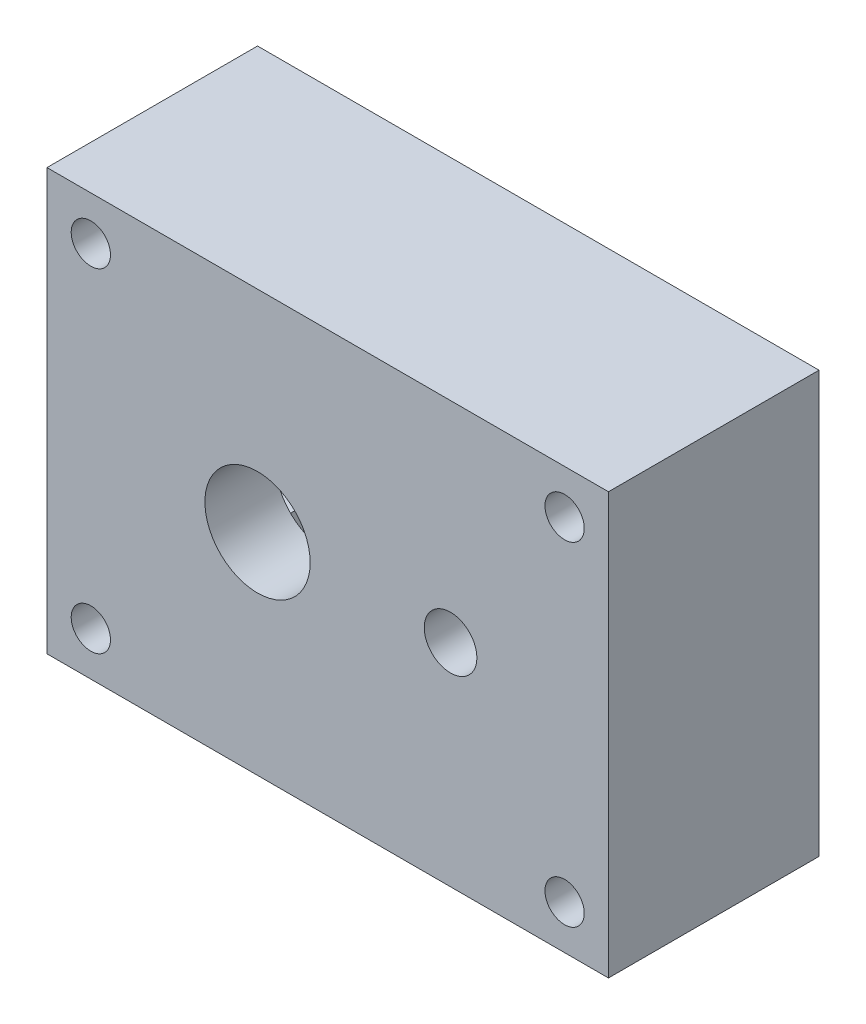
SolidWorks part; units mm, degrees
ref_plane "Front Plane" through (0, 0, 0) normal (0, 0, 1) x (1, 0, 0)
ref_plane "Top Plane" through (0, 0, 0) normal (0, 1, 0) x (1, 0, 0)
ref_plane "Right Plane" through (0, 0, 0) normal (1, 0, 0) x (0, 0, -1)
sketch "Sketch1" plane through (0, 0, 0) normal (0, 0, 1) x (1, 0, 0)
  line L1 (-19.05, 19.05) -> (31.75, 19.05)
  line L2 (-19.05, 19.05) -> (-19.05, -19.05)
  line L3 (-19.05, -19.05) -> (31.75, -19.05)
  line L4 (31.75, 19.05) -> (31.75, -19.05)
  dimension "D1" = 50.8
  dimension "D2" = 38.1
  dimension "D3" = 19.05
  dimension "D4" = 19.05
extrude "Boss-Extrude1" add sketch "Sketch1" against normal blind 19.05
sketch "Sketch2" plane through (0, 0, -19.05) normal (0, 0, -1) x (-1, 0, 0)
  line L8 (15.875, -15.875) -> (15.875, 15.875)
  line L9 (15.875, 15.875) -> (-28.575, 15.875)
  line L10 (-28.575, 15.875) -> (-28.575, -15.875)
  line L11 (-28.575, -15.875) -> (15.875, -15.875)
  line L12 (15.875, -15.875) -> (15.875, 15.875)
  line L13 (15.875, 15.875) -> (-28.575, 15.875)
  line L14 (-28.575, 15.875) -> (-28.575, -15.875)
  line L15 (-28.575, -15.875) -> (15.875, -15.875)
  dimension "D1" = 3.175
extrude "Cut-Extrude1" cut sketch "Sketch2" against normal blind 12.7
sketch "Sketch3" plane through (0, 0, 0) normal (0, 0, 1) x (1, 0, 0)
  circle A0 centre (0, 0) radius 4.7625
  circle A1 centre (17.4623, 0.083) radius 2.3813
  dimension "D1" = 9.525
  dimension "D2" = 4.7625
extrude "Cut-Extrude2" cut sketch "Sketch3" against normal through all
sketch "Sketch4" plane through (0, 0, -6.35) normal (0, 0, -1) x (-1, 0, 0)
  line L1 (-31.75, 19.05) -> (-23.8125, 19.05)
  line L2 (-31.75, 19.05) -> (-31.75, 11.1125)
  line L3 (-31.75, 11.1125) -> (-23.8125, 11.1125)
  line L4 (-23.8125, 19.05) -> (-23.8125, 11.1125)
  line L5 (19.05, 19.05) -> (11.1125, 19.05)
  line L6 (19.05, 19.05) -> (19.05, 11.1125)
  line L7 (19.05, 11.1125) -> (11.1125, 11.1125)
  line L8 (11.1125, 19.05) -> (11.1125, 11.1125)
  line L9 (19.05, -19.05) -> (11.1125, -19.05)
  line L10 (19.05, -19.05) -> (19.05, -11.1125)
  line L11 (19.05, -11.1125) -> (11.1125, -11.1125)
  line L12 (11.1125, -19.05) -> (11.1125, -11.1125)
  line L13 (-31.75, -19.05) -> (-23.8125, -19.05)
  line L14 (-31.75, -19.05) -> (-31.75, -11.1125)
  line L15 (-31.75, -11.1125) -> (-23.8125, -11.1125)
  line L16 (-23.8125, -19.05) -> (-23.8125, -11.1125)
  dimension "D1" = 7.9375
  dimension "D2" = 7.9375
  dimension "D3" = 7.9375
  dimension "D4" = 7.9375
  dimension "D5" = 7.9375
  dimension "D6" = 7.9375
  dimension "D7" = 7.9375
  dimension "D8" = 7.9375
extrude "Boss-Extrude2" add sketch "Sketch4" along normal blind 12.7
sketch "Sketch5" plane through (0, 0, -19.05) normal (0, 0, -1) x (-1, 0, 0)
  line L0 (-31.75, 19.05) -> (19.05, 19.05) construction
  line L1 (-31.75, -19.05) -> (-31.75, 19.05) construction
  line L2 (19.05, -19.05) -> (-31.75, -19.05) construction
  line L3 (19.05, 19.05) -> (19.05, -19.05) construction
  circle A0 centre (-27.7812, 15.0813) radius 1.778
  circle A1 centre (15.0813, 15.0813) radius 1.778
  circle A2 centre (15.0813, -15.0813) radius 1.778
  circle A3 centre (-27.7812, -15.0813) radius 1.778
  dimension "D1" = 3.556
  dimension "D2" = 3.556
  dimension "D3" = 3.556
  dimension "D4" = 3.556
  dimension "D5" = 3.9688
  dimension "D6" = 3.9688
  dimension "D7" = 3.9688
  dimension "D8" = 3.9688
  dimension "D9" = 3.9688
  dimension "D10" = 3.9688
  dimension "D11" = 3.9688
  dimension "D12" = 3.9688
extrude "Cut-Extrude3" cut sketch "Sketch5" against normal through all
